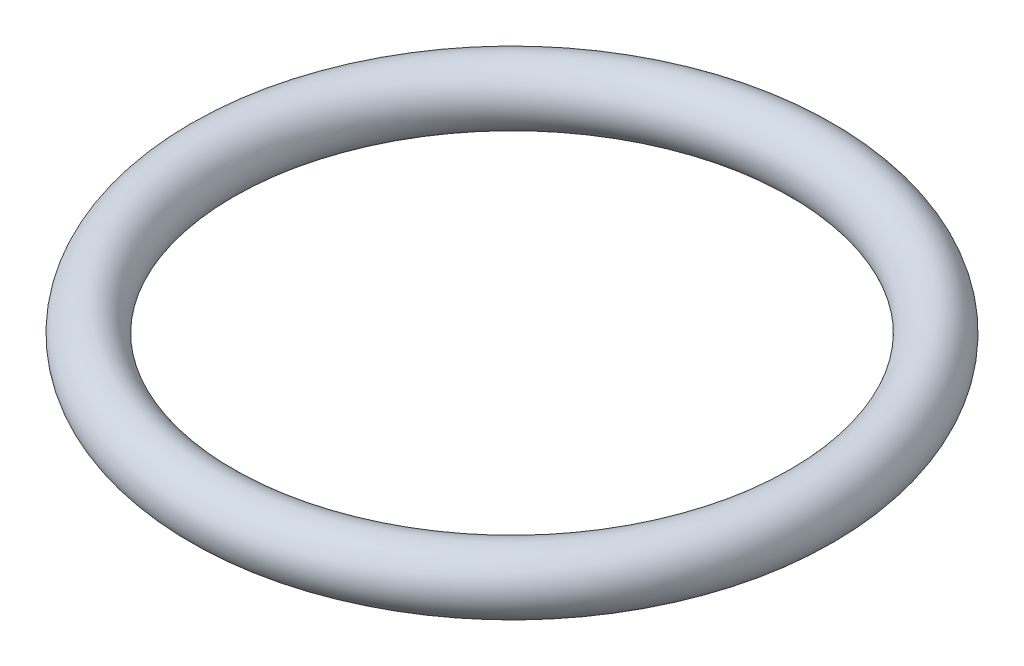
SolidWorks part; units mm, degrees
material "橡胶"
ref_plane "前视基准面" through (0, 0, 0) normal (0, 0, 1) x (1, 0, 0)
ref_plane "上视基准面" through (0, 0, 0) normal (0, 1, 0) x (1, 0, 0)
ref_plane "右视基准面" through (0, 0, 0) normal (1, 0, 0) x (0, 0, -1)
sketch "草图1" plane through (0, 0, 0) normal (0, 1, 0) x (1, 0, 0)
  circle A0 centre (0, 0) radius 25
sketch "草图2" plane through (0, 0, 0) normal (0, 0, 1) x (1, 0, 0)
  line L0 (25, 0) -> (-25, 0) construction
  circle A0 centre (-25, 0) radius 2.5
sweep "扫描1" add profiles "草图2" path "草图1"
